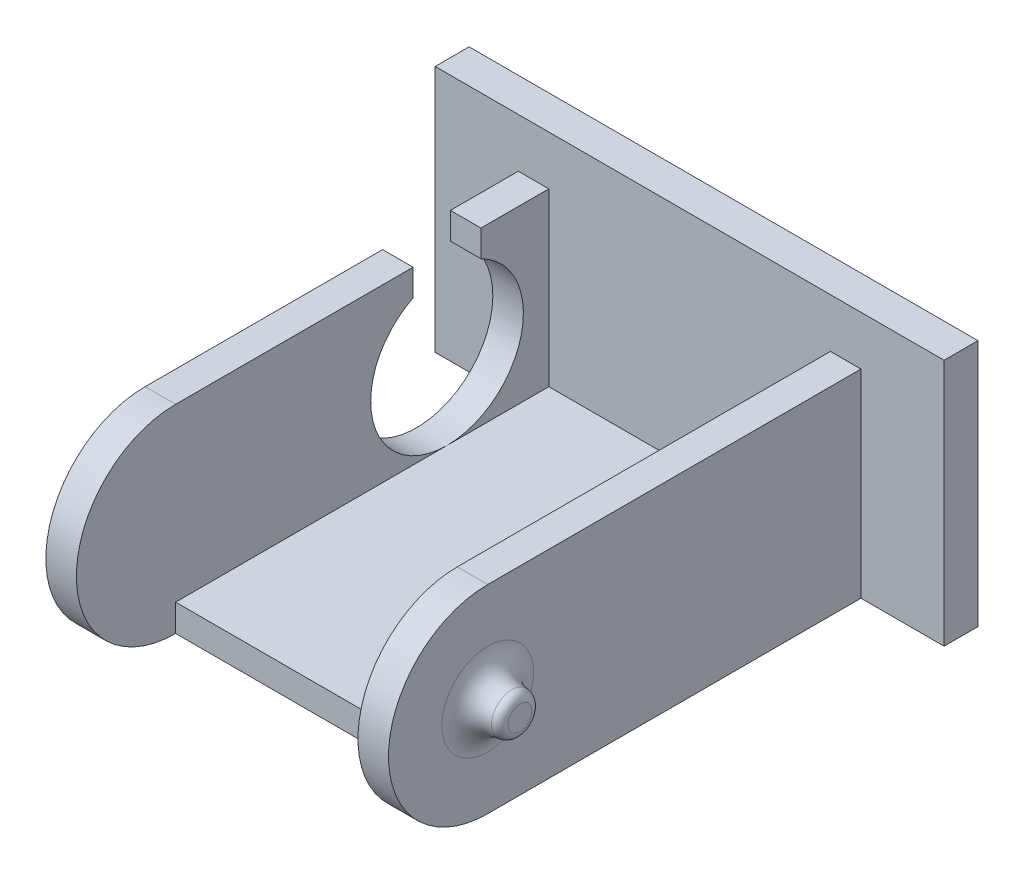
SolidWorks part; units mm, degrees
ref_plane "Front Plane" through (0, 0, 0) normal (0, 0, 1) x (1, 0, 0)
ref_plane "Top Plane" through (0, 0, 0) normal (0, 1, 0) x (1, 0, 0)
ref_plane "Right Plane" through (0, 0, 0) normal (1, 0, 0) x (0, 0, -1)
sketch "Sketch1" plane through (0, 0, 0) normal (0, 1, 0) x (1, 0, 0)
  line L1 (-10.1, 6) -> (10.1, 6)
  line L2 (-10.1, 6) -> (-10.1, -6)
  line L3 (-10.1, -6) -> (10.1, -6)
  line L4 (10.1, 6) -> (10.1, -6)
  line L5 (-10.1, 6) -> (10.1, -6) construction
  line L6 (-10.1, -6) -> (10.1, 6) construction
  point P0 (0, 0)
  dimension "D1" = 20.2
  dimension "D2" = 12
extrude "Boss-Extrude1" add sketch "Sketch1" along normal blind 1.6
sketch "Sketch2" plane through (10.1, 0, 0) normal (1, 0, 0) x (0, 0, -1)
  line L0 (-6, 11.7) -> (6, 11.7) construction
  line L1 (-6, 0) -> (6, 0) construction
  line L2 (-6, 11.7) -> (6, 11.7)
  line L3 (6, 11.7) -> (6, 0)
  line L4 (6, 0) -> (-6, 0)
  arc A0 (-6, 11.7) -> (-6, 0) centre (-6, 5.85) ccw
  dimension "D1" = 11.7
extrude "Boss-Extrude2" add sketch "Sketch2" against normal blind 1.8
sketch "Sketch3" plane through (10.1, 0, 0) normal (1, 0, 0) x (0, 0, -1)
  circle A0 centre (-6, 5.85) radius 1.2
  dimension "D1" = 2.4
extrude "Boss-Extrude3" add sketch "Sketch3" along normal blind 1.9
fillet "Fillet1" radius 1.5 1 edges at (10.1, 5.85, 7.2)
fillet "Fillet2" radius 0.5 1 edges at (12, 5.85, 4.8)
mirror "Mirror2" about plane through (0, 0, 0) normal (1, 0, 0) of "Boss-Extrude3", "Boss-Extrude2"
fillet "Fillet3" radius 1.5 1 edges at (-10.1, 5.85, 4.8)
fillet "Fillet4" radius 0.5 1 edges at (-12, 5.85, 4.8)
sketch "Sketch4" plane through (0, 0, -6) normal (0, 0, -1) x (-1, 0, 0)
  line L8 (10.1, 0) -> (10.1, 11.7)
  line L9 (10.1, 11.7) -> (8.3, 11.7)
  line L10 (8.3, 11.7) -> (8.3, 1.6)
  line L11 (8.3, 1.6) -> (-8.3, 1.6)
  line L12 (-8.3, 1.6) -> (-8.3, 11.7)
  line L13 (-8.3, 11.7) -> (-10.1, 11.7)
  line L14 (-10.1, 11.7) -> (-10.1, 0)
  line L15 (-10.1, 0) -> (10.1, 0)
  line L16 (10.1, 0) -> (10.1, 11.7)
  line L17 (10.1, 11.7) -> (8.3, 11.7)
  line L18 (8.3, 11.7) -> (8.3, 1.6)
  line L19 (8.3, 1.6) -> (-8.3, 1.6)
  line L20 (-8.3, 1.6) -> (-8.3, 11.7)
  line L21 (-8.3, 11.7) -> (-10.1, 11.7)
  line L22 (-10.1, 11.7) -> (-10.1, 0)
  line L23 (-10.1, 0) -> (10.1, 0)
  dimension "D1" = 0
extrude "Boss-Extrude4" add sketch "Sketch4" along normal blind 10
sketch "Sketch5" plane through (0, 0, -16) normal (0, 0, -1) x (-1, 0, 0)
  line L0 (-10.1, 5.85) -> (10.1, 5.85) construction
  line L1 (-10.1, 11.7) -> (-10.1, 0) construction
  line L2 (10.1, 0) -> (10.1, 11.7) construction
  line L4 (-15, 14.6) -> (15, 14.6)
  line L5 (-15, 14.6) -> (-15, -2.9)
  line L6 (-15, -2.9) -> (15, -2.9)
  line L7 (15, 14.6) -> (15, -2.9)
  line L8 (-15, 14.6) -> (15, -2.9) construction
  line L9 (-15, -2.9) -> (15, 14.6) construction
  point P6 (0, 5.85)
  dimension "D1" = 30
  dimension "D2" = 17.5
extrude "Boss-Extrude5" add sketch "Sketch5" along normal blind 2
sketch "Sketch7" plane through (-8.3, 0, 0) normal (1, 0, 0) x (0, 0, -1)
  line L0 (16, 1.6) -> (-6, 1.6) construction
  line L1 (16, 11.7) -> (16, 1.6) construction
  line L2 (16, 11.7) -> (-6, 11.7) construction
  line L5 (8, 11.7) -> (12, 11.7)
  line L9 (8, 10.1311) -> (8, 11.7)
  line L12 (12, 10.1311) -> (12, 11.7)
  arc A0 (8, 10.1311) -> (12, 10.1311) centre (10, 6.1) ccw
  point P1 (10, 11.7)
  dimension "D1" = 9
  dimension "D2" = 6
  dimension "D3" = 4
  dimension "D4" = 1.5689
  dimension "D5" = 1.5689
extrude "Cut-Extrude1" cut sketch "Sketch7" against normal blind 2
sketch "Sketch8" plane through (0, 0, -18) normal (0, 0, -1) x (-1, 0, 0)
  line L0 (15, -2.9) -> (15, 14.6) construction
  line L1 (-15, -2.9) -> (15, -2.9)
  line L2 (-15, -2.9) -> (-15, 0)
  line L3 (-15, 0) -> (15, 0)
  line L4 (15, -2.9) -> (15, 0)
  dimension "D1" = 2.9
extrude "Cut-Extrude3" cut sketch "Sketch8" against normal blind 2
